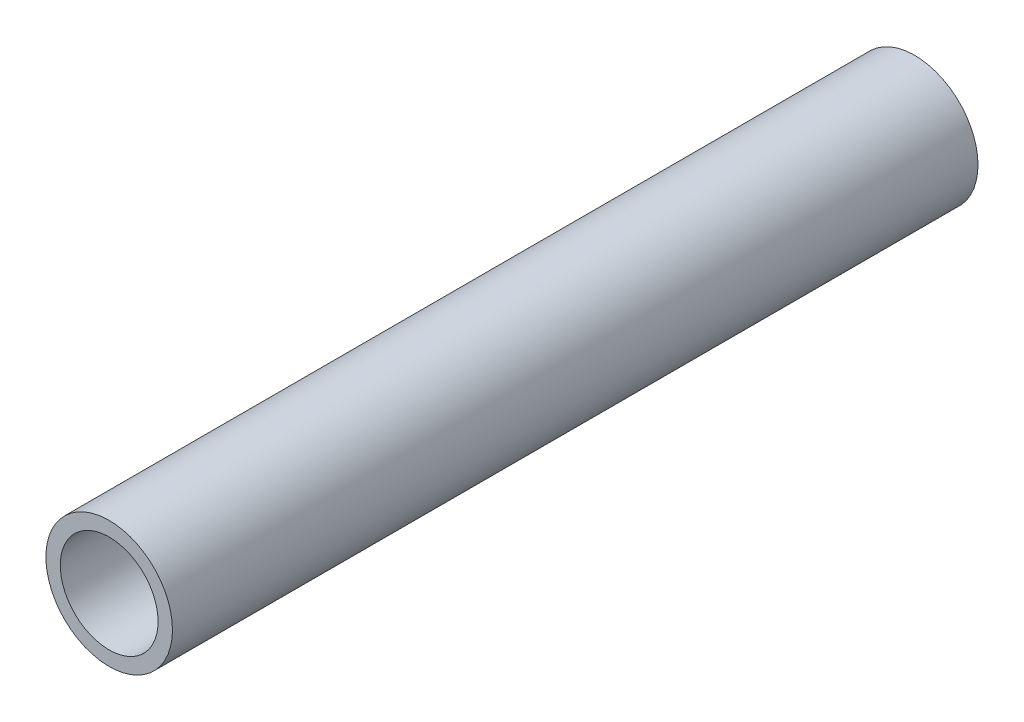
SolidWorks part; units mm, degrees
material "PVC 0.007 Plasticized"
ref_plane "Front Plane" through (0, 0, 0) normal (0, 0, 1) x (1, 0, 0)
ref_plane "Top Plane" through (0, 0, 0) normal (0, 1, 0) x (1, 0, 0)
ref_plane "Right Plane" through (0, 0, 0) normal (1, 0, 0) x (0, 0, -1)
sketch "Sketch1" plane through (0, 0, 0) normal (0, 0, 1) x (1, 0, 0)
  circle A0 centre (0, 0) radius 11
  circle A1 centre (0, 0) radius 8.5
extrude "Boss-Extrude1" add sketch "Sketch1" along normal blind 140
